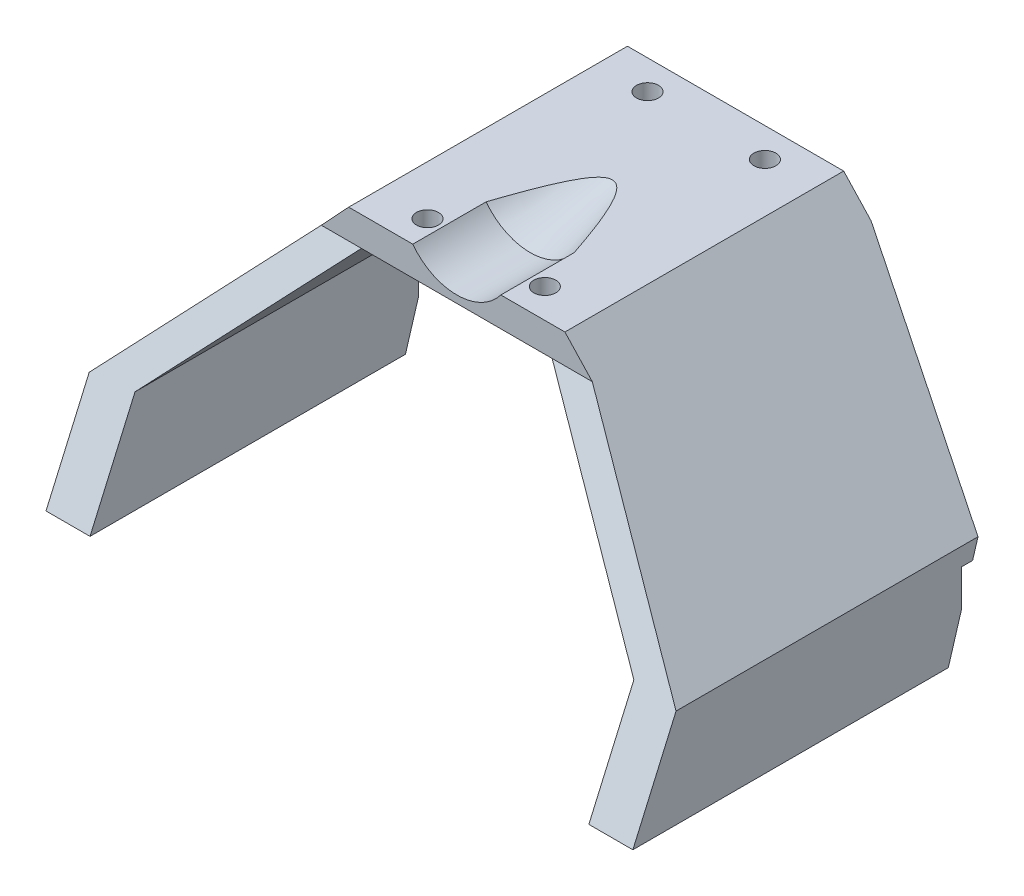
SolidWorks part; units mm, degrees
ref_plane "Front" through (0, 0, 0) normal (0, 0, 1) x (1, 0, 0)
ref_plane "Top" through (0, 0, 0) normal (0, 1, 0) x (1, 0, 0)
ref_plane "Right" through (0, 0, 0) normal (1, 0, 0) x (0, 0, -1)
sketch "Sketch1" plane through (0, 0, 0) normal (0, 0, 1) x (1, 0, 0)
  line L0 (0, 0) -> (0, 40.5) construction
  line L1 (14.7382, 40.5) -> (-14.7382, 40.5)
  line L2 (-14.7382, 40.5) -> (-40, 13.4338)
  line L3 (-40, 13.4338) -> (-40, 0)
  line L4 (-40, 0) -> (-34, 0)
  line L5 (-34, 0) -> (-34, 14)
  line L6 (-34, 14) -> (-13, 36.5)
  line L7 (-13, 36.5) -> (13, 36.5)
  line L8 (34, 14) -> (13, 36.5)
  line L9 (34, 0) -> (34, 14)
  line L10 (40, 0) -> (34, 0)
  line L11 (40, 13.4338) -> (40, 0)
  line L12 (14.7382, 40.5) -> (40, 13.4338)
  point P17 (0, 36.5)
  dimension "D1" = 40.5
  dimension "D2" = 6
  dimension "D3" = 26
  dimension "D4" = 80
  dimension "D5" = 4
  dimension "D6" = 4
  dimension "D7" = 14
extrude "Boss-Extrude1" add sketch "Sketch1" along normal blind 54
sketch "Sketch2" plane through (0, 0, 0) normal (1, 0, 0) x (0, 0, -1)
  line L0 (0, 36.5) -> (-11, 0)
  line L1 (0, 40.5) -> (0, 13.4338) construction
  line L2 (-54, 0) -> (0, 0) construction
  line L3 (-11, 0) -> (0, 0)
  line L4 (0, 0) -> (0, 36.5)
  line L5 (-38, 40.5) -> (-38, 36.5)
  line L6 (-54, 40.5) -> (0, 40.5) construction
  line L7 (-38, 36.5) -> (-54, 0)
  line L8 (-54, 0) -> (-54, 40.5)
  line L9 (-54, 40.5) -> (-38, 40.5)
  dimension "D1" = 11
  dimension "D2" = 38
extrude "Cut-Extrude1" cut sketch "Sketch2" against normal through all both and the other way through all
sketch "Sketch3" plane through (0, 40.5, 0) normal (0, 1, 0) x (1, 0, 0)
  line L0 (14.7382, -38) -> (14.7382, 0) construction
  line L1 (8, -34) -> (-8, -34)
  line L2 (8, -34) -> (8, -4)
  line L3 (8, -4) -> (-8, -4)
  line L4 (-8, -34) -> (-8, -4)
  line L5 (-14.7382, -38) -> (14.7382, -38) construction
  point P5 (8, -19)
  point P8 (14.7382, -19)
  point P9 (0, -4)
  point P12 (0, -38)
  dimension "D1" = 30
  dimension "D2" = 16
hole_wizard "Ø3.0mm Dowel Hole1" positions "3DSketch1" profile "Sketch4" hole size "Ø3.0" standard "ISO" end condition up to next
sketch3d "3DSketch1"
  point P0 (-8, 40.5, 4)
  point P3 (8, 40.5, 4)
  point P6 (8, 40.5, 34)
  point P9 (-8, 40.5, 34)
sketch "Sketch4" plane through (-8, 40.5, 4) normal (1, 0, 0) x (0, 0, 1)
  line L0 (0, 0) -> (0, 4)
  line L1 (0, 4) -> (1.5, 4)
  line L2 (1.5, 4) -> (1.5, 0)
  line L5 (1.5, 0) -> (0, 0)
  line L11 (0, -6.35) -> (0, 107.95) construction
  dimension "Thru Hole Dia." = 3
  dimension "Thru Hole Depth" = 4
sketch "Sketch5" plane through (0, 0, 0) normal (0, -1, 0) x (1, 0, 0)
  line L0 (40, 54) -> (40, 11) construction
  line L1 (-37, 48) -> (37, 48)
  line L2 (-37, 48) -> (-37, 17)
  line L3 (-37, 17) -> (37, 17)
  line L4 (37, 48) -> (37, 17)
  point P4 (37, 32.5)
  point P7 (40, 32.5)
  point P8 (0, 17)
  dimension "D1" = 31
  dimension "D2" = 74
hole_wizard "Ø3.0mm Dowel Hole2" positions "3DSketch2" profile "Sketch7" hole size "Ø3.0" standard "ISO"
sketch3d "3DSketch2"
  point P0 (-37, 0, 48)
  point P3 (37, 0, 48)
  point P6 (37, 0, 17)
  point P9 (-37, 0, 17)
sketch "Sketch7" plane through (-37, 0, 48) normal (1, 0, 0) x (0, 0, -1)
  line L0 (0, 0) -> (0, 10.8712)
  line L1 (0, 10.8712) -> (1.45, 10)
  line L2 (1.45, 10) -> (1.45, 0)
  line L5 (1.45, 0) -> (0, 0)
  line L10 (0, 10.8712) -> (-1.45, 10) construction
  line L11 (0, -6.35) -> (0, 107.95) construction
  dimension "Hole Dia." = 2.9
  dimension "Hole Depth" = 10
  dimension "Drill Angle" = 118
sketch "Sketch8" plane through (-40, 0, 0) normal (-1, 0, 0) x (0, 0, 1)
  line L0 (6.9515, 13.4338) -> (11, 0) construction
  line L1 (6.4225, 11) -> (9.1918, 11)
  line L2 (6.4225, 11) -> (6.4225, 6)
  line L3 (6.4225, 6) -> (9.1918, 6)
  line L4 (9.1918, 11) -> (9.1918, 6)
  line L5 (54, 0) -> (11, 0) construction
  dimension "D1" = 6
  dimension "D2" = 5
extrude "Cut-Extrude2" cut sketch "Sketch8" against normal through all
sketch "Sketch10" plane through (0, 0, 38) normal (0, 0, 1) x (1, 0, 0)
  line L0 (-13, 36.5) -> (13, 36.5) construction
  line L1 (-14.7382, 40.5) -> (14.7382, 40.5) construction
  circle A0 centre (0, 45) radius 7.5
  point P2 (0, 45.3091)
  point P5 (0, 0)
  point P10 (0, 0)
  point P11 (0, 40.5)
  dimension "D1" = 15
  dimension "D2" = 8.5
extrude "Cut-Extrude3" cut sketch "Sketch10" against normal blind 10
sketch "Sketch11" plane through (0, 0, 28) normal (0, 0, 1) x (1, 0, 0)
  circle A0 centre (0, 45) radius 7.5
  arc A1 (-6, 40.5) -> (6, 40.5) centre (0, 45) ccw construction
extrude "Cut-Extrude4" cut sketch "Sketch11" against normal blind 15 draft 15
